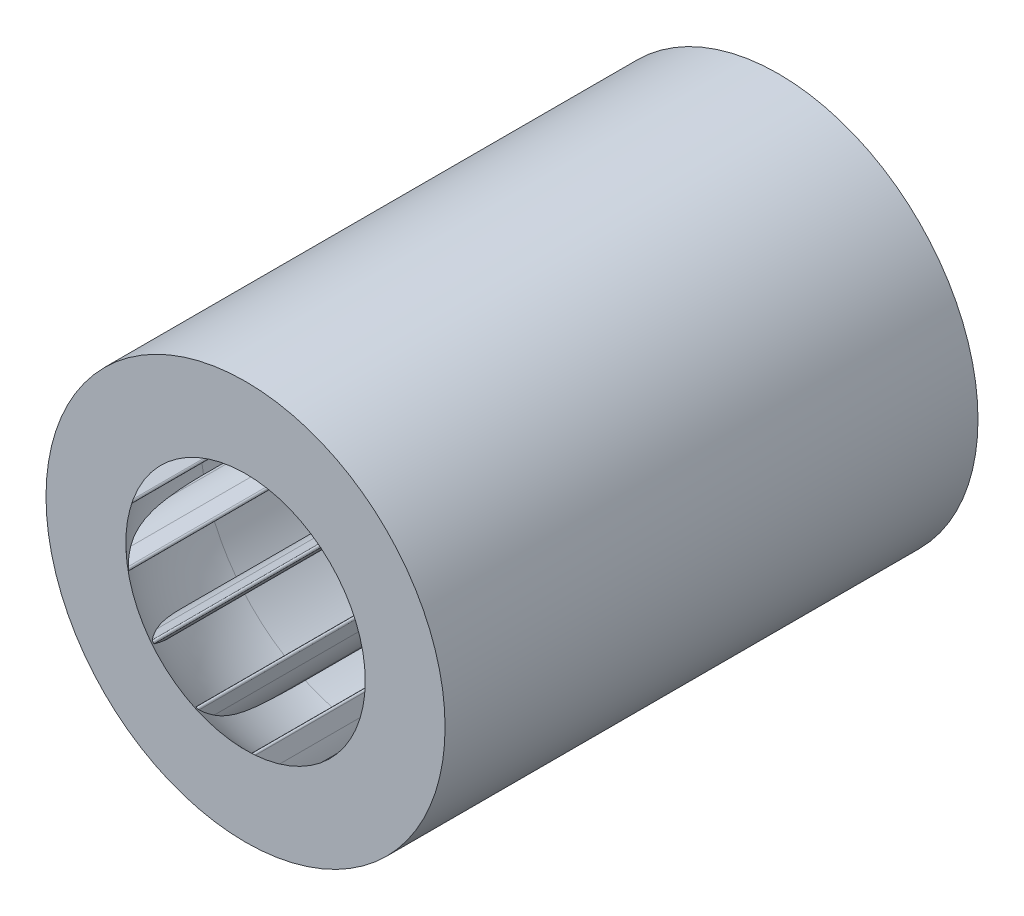
SolidWorks part; units mm, degrees
ref_plane "前视基准面" through (0, 0, 0) normal (0, 0, 1) x (1, 0, 0)
ref_plane "上视基准面" through (0, 0, 0) normal (0, 1, 0) x (1, 0, 0)
ref_plane "右视基准面" through (0, 0, 0) normal (1, 0, 0) x (0, 0, -1)
other "Configuration Table"
sketch "草图1" plane through (0, 0, 0) normal (0, 0, 1) x (1, 0, 0)
  circle A0 centre (0, 0) radius 25
  circle A1 centre (0, 0) radius 20
  dimension "D1" = 50
  dimension "D2" = 40
sketch "草图2" plane through (0, 0, 0) normal (1, 0, 0) x (0, 0, -1)
  line L0 (0, 0) -> (30.9602, 0) construction
  line L1 (16.7705, 22.5) -> (66.7705, 22.5)
  line L2 (0, 20) -> (0, -20) construction
  line L6 (0, 15) -> (0, 25)
  line L7 (0, 25) -> (66.7705, 25)
  line L8 (66.7705, 22.5) -> (66.7705, 25)
  circle A0 centre (16.7705, 0) radius 22.5 construction
  arc A2 (16.7705, 22.5) -> (0, 15) centre (16.7705, 0) ccw
  point P3 (0, 15)
  dimension "D2" = 45
  dimension "D1" = 15
  dimension "D3" = 50
  dimension "D4" = 25
revolve "旋转1" add sketch "草图2" angle 360 about L0
sketch "草图3" plane through (0, 0, 0) normal (0, 0, 1) x (1, 0, 0)
  line L0 (0, 0.0206) -> (0, 9.6346) construction
  line L1 (-0.1961, -15.9806) -> (-0.6078, -18.0388)
  line L2 (-0.6078, -21.9612) -> (-0.1961, -24.0194)
  line L3 (0.1961, -24.0194) -> (0.6078, -21.9612)
  line L4 (0.6078, -18.0388) -> (0.1961, -15.9806)
  line L5 (-1, -20) -> (1, -20) construction
  circle A0 centre (0, 0) radius 20 construction
  circle A1 centre (0, 0) radius 25 construction
  arc A2 (0.6078, -21.9612) -> (0.6078, -18.0388) centre (-9.198, -20) ccw
  arc A3 (-0.6078, -18.0388) -> (-0.6078, -21.9612) centre (9.198, -20) ccw
  arc A4 (0.1961, -24.0194) -> (-0.1961, -24.0194) centre (0, -23.9802) cw
  arc A5 (0.1961, -15.9806) -> (-0.1961, -15.9806) centre (0, -16.0198) ccw
  point P1 (0, -20)
  point P20 (0, -25)
  point P23 (0, -15)
  dimension "D2" = 10
  dimension "D3" = 0.2
  dimension "D1" = 2
extrude "凸台-拉伸1" add sketch "草图3" against normal through all
pattern_circular "阵列(圆周)1" count 14 over 360 about axis through (0, 0, 0) along (0, 0, 1) of "凸台-拉伸1"
equation "\"outside diameter\"= 50"
equation "\"inside diameter\"= 40"
equation "\"D1@草图1\"=\"outside diameter\""
equation "\"D2@草图1\"=\"inside diameter\""
equation "\"intake output diameter\"= 30"
equation "\"outside radius\"= \"outside diameter\" / 2"
equation "\"inside radius\"= \"inside diameter\" / 2"
equation "\"D1@草图2\"=\"intake output diameter\"/2"
equation "\"D2@草图2\"=\"outside diameter\"-5"
equation "\"D4@草图2\"=\"outside radius\""
